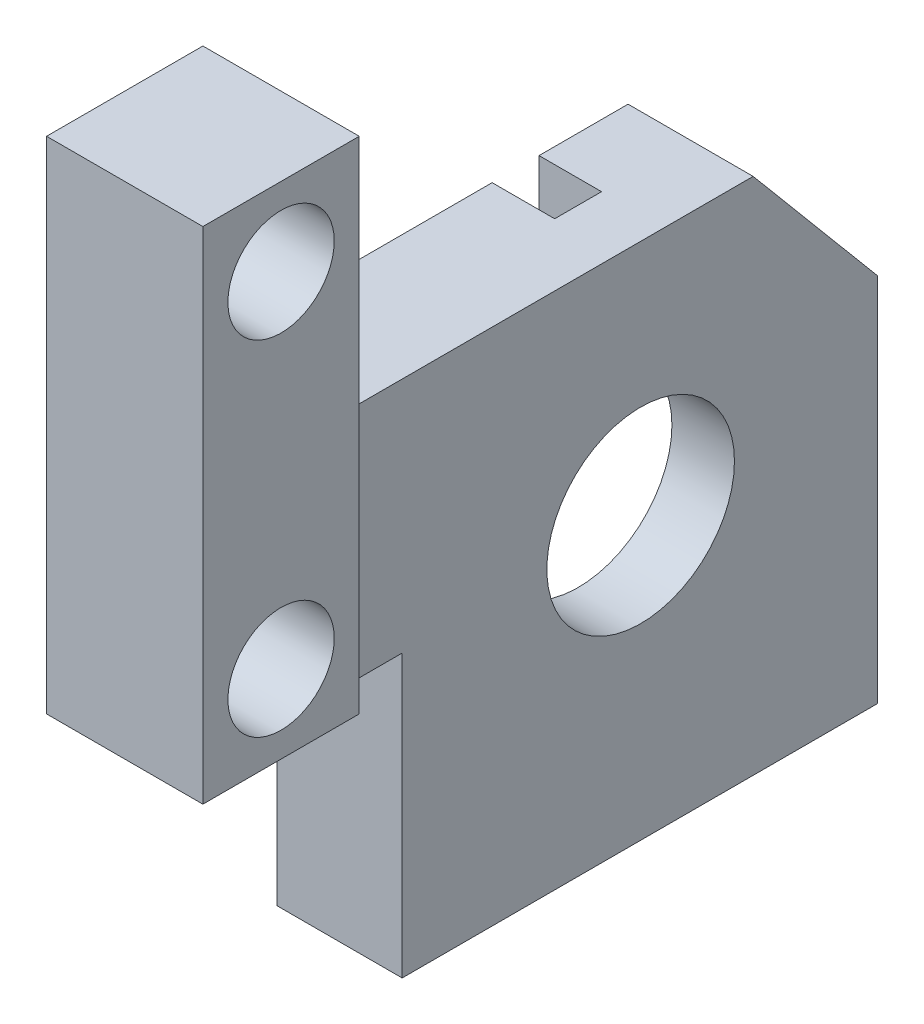
SolidWorks part; units mm, degrees
ref_plane "Front Plane" through (0, 0, 0) normal (0, 0, 1) x (1, 0, 0)
ref_plane "Top Plane" through (0, 0, 0) normal (0, 1, 0) x (1, 0, 0)
ref_plane "Right Plane" through (0, 0, 0) normal (1, 0, 0) x (0, 0, -1)
sketch "Sketch1" plane through (0, 0, 0) normal (1, 0, 0) x (0, 0, -1)
  line L0 (-6.1093, 3.9687) -> (-3.1473, 7.4987)
  line L1 (-3.1473, 7.4987) -> (-1.2321, 7.4987)
  line L2 (-6.1093, 3.9687) -> (-6.1093, -5.0913)
  line L3 (-6.1093, -5.0913) -> (-3.9821, -5.0913)
  line L4 (5.0907, 4.0335) -> (5.0907, -5.0913)
  line L5 (-4.0799, 9.4987) -> (-1.2321, 9.4987)
  line L6 (-8.1093, 4.6966) -> (-8.1093, -7.0913)
  line L7 (-8.1093, -7.0913) -> (-3.9821, -7.0913)
  line L8 (7.0907, 4.7614) -> (7.0907, -7.0913)
  line L9 (5.0907, 4.0335) -> (2.1831, 7.4987)
  line L10 (-8.1093, 4.6966) -> (-4.0799, 9.4987)
  line L11 (3.1157, 9.4987) -> (7.0907, 4.7614)
  line L12 (0.2679, 7.4987) -> (0.2679, 9.4987)
  line L13 (-1.2321, 7.4987) -> (-1.2321, 9.4987)
  line L14 (3.0179, -5.0913) -> (3.0179, -7.0913)
  line L15 (-3.9821, -5.0913) -> (-3.9821, -7.0913)
  line L16 (-0.4821, 1.9087) -> (-0.4821, -6.5913) construction
  line L17 (-8.1093, 1.9087) -> (7.0907, 1.9087) construction
  line L18 (0.2679, 9.4987) -> (3.1157, 9.4987)
  line L19 (0.2679, 7.4987) -> (2.1831, 7.4987)
  line L20 (3.0179, -5.0913) -> (5.0907, -5.0913)
  line L21 (3.0179, -7.0913) -> (7.0907, -7.0913)
  point P20 (1.2255, 7.4987)
  dimension "D1" = 2
  dimension "D2" = 2
  dimension "D3" = 2
  dimension "D4" = 2
  dimension "D5" = 2
  dimension "D6" = 2
  dimension "D7" = 40
  dimension "D8" = 40
  dimension "D9" = 3.53
  dimension "D10" = 3.5
  dimension "D11" = 7
  dimension "D12" = 3.5
  dimension "D13" = 0.75
  dimension "D14" = 0.75
  dimension "D15" = 5.59
  dimension "D16" = 11.2
sketch "Sketch2" plane through (0, 0, 0) normal (1, 0, 0) x (0, 0, -1)
  line L0 (-8.1093, -7.0913) -> (-8.1093, 4.6966)
  line L1 (-8.1093, 4.6966) -> (-4.0799, 9.4987)
  line L2 (-4.0799, 9.4987) -> (3.1157, 9.4987)
  line L3 (3.1157, 9.4987) -> (7.0907, 4.7614)
  line L4 (7.0907, 4.7614) -> (7.0907, -7.0913)
  line L5 (7.0907, -7.0913) -> (-8.1093, -7.0913)
extrude "Boss-Extrude1" add sketch "Sketch2" against normal blind 2
extrude "Boss-Extrude2" add sketch "Sketch1" along normal blind 2
sketch "Sketch3" plane through (0, 0, 0) normal (1, 0, 0) x (0, 0, -1)
  circle A0 centre (-0.4821, 1.9087) radius 3
extrude "Cut-Extrude1" cut sketch "Sketch3" against normal blind 2
sketch "Sketch4" plane through (2, 0, 0) normal (1, 0, 0) x (0, 0, -1)
  line L0 (-15.4821, 1.9087) -> (-8.1093, 1.9087)
  line L1 (-10.4821, 17.9087) -> (-15.4821, 17.9087) construction
  line L6 (-15.4821, 17.9087) -> (-15.4821, 1.9087)
  line L8 (-4.0799, 9.4987) -> (-8.1093, 4.6966)
  line L14 (-15.4821, 17.9087) -> (-10.4821, 17.9087)
  line L17 (-10.4821, 17.9087) -> (-10.4821, 9.4987)
  line L18 (-10.4821, 9.4987) -> (-4.0799, 9.4987)
  line L19 (-8.1093, 4.6966) -> (-8.1093, 1.9087)
  circle A1 centre (-12.9821, 4.4087) radius 1.7
  circle A2 centre (-12.9821, 15.4087) radius 1.7
  dimension "D7" = 3.4
  dimension "D8" = 3.4
  dimension "D1" = 2.5
  dimension "D2" = 2.5
  dimension "D3" = 2.5
  dimension "D5" = 2.5
extrude "Boss-Extrude3" add sketch "Sketch4" against normal blind 5
sketch "Sketch5" plane through (-3, 0, 0) normal (-1, 0, 0) x (0, 0, 1)
  line L0 (10.4821, 9.4987) -> (10.4821, 1.9087)
  line L1 (15.4821, 1.9087) -> (8.1093, 1.9087) construction
  line L2 (10.4821, 1.9087) -> (8.1093, 1.9087)
  line L3 (8.1093, 1.9087) -> (8.1093, 4.6966)
  line L4 (8.1093, 4.6966) -> (4.0799, 9.4987)
  line L5 (4.0799, 9.4987) -> (10.4821, 9.4987)
extrude "Cut-Extrude2" cut sketch "Sketch5" against normal blind 1
ref_plane "Plane1" through (10, 0, 0) normal (1, 0, 0) x (0, 0, -1)
mirror "Mirror2" about plane through (10, 0, 0) normal (1, 0, 0) of bodies 105
delete or keep bodies "Body-Delete/Keep 1" type delete bodies bodies 105
